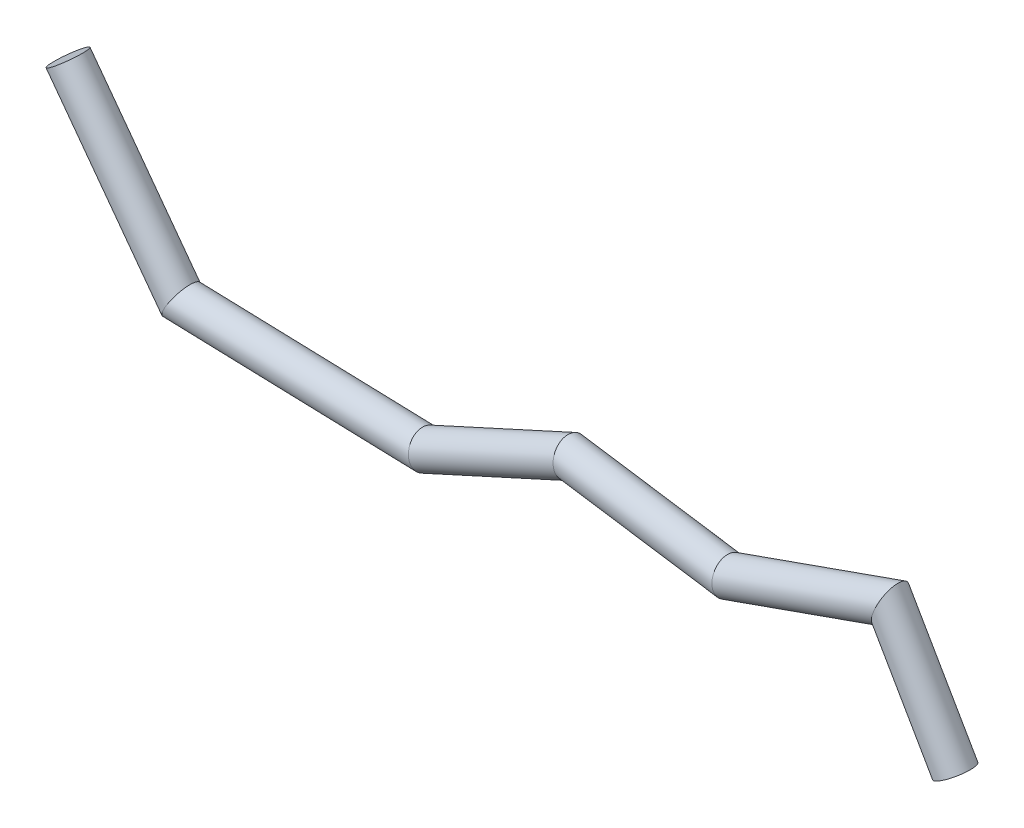
SolidWorks part; units mm, degrees
ref_plane "Front Plane" through (0, 0, 0) normal (0, 0, 1) x (1, 0, 0)
ref_plane "Top Plane" through (0, 0, 0) normal (0, 1, 0) x (1, 0, 0)
ref_plane "Right Plane" through (0, 0, 0) normal (1, 0, 0) x (0, 0, -1)
sketch "Sketch2" plane through (0, 0, 0) normal (0, 0, 1) x (1, 0, 0)
  line L0 (-121.3218, 25.3446) -> (-79.4962, -31.1614)
  line L1 (-79.4962, -31.1614) -> (11.0796, -33.9313)
  line L2 (11.0796, -33.9313) -> (64.5388, -9.5562)
  line L3 (64.5388, -9.5562) -> (123.2607, -18.4199)
  line L4 (123.2607, -18.4199) -> (182.8136, 2.6314)
  line L5 (182.8136, 2.6314) -> (206.9118, -39.1941)
sweep "Sweep1" add path "Sketch2" circular profile diameter 12.7 parameters "D3"=12.7
